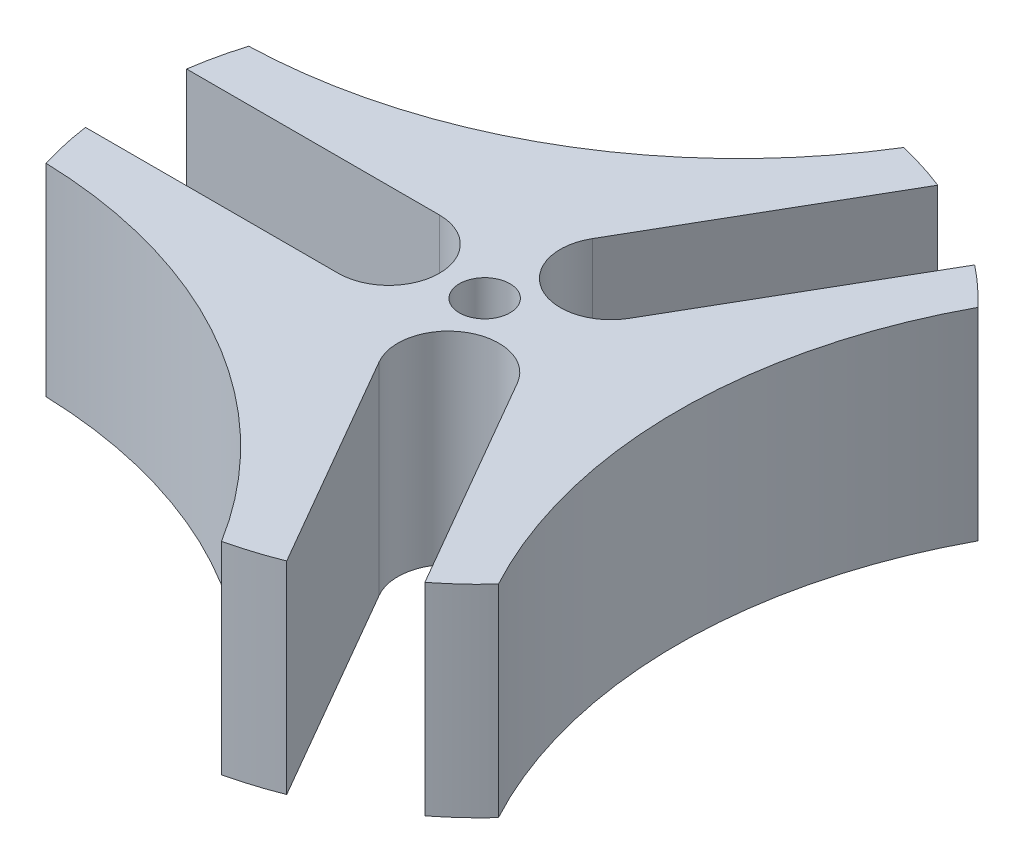
SolidWorks part; units mm, degrees
ref_plane "前基準面" through (0, 0, 0) normal (0, 0, 1) x (1, 0, 0)
ref_plane "上基準面" through (0, 0, 0) normal (0, 1, 0) x (1, 0, 0)
ref_plane "右基準面" through (0, 0, 0) normal (1, 0, 0) x (0, 0, -1)
sketch "草圖1" plane through (0, 0, 0) normal (0, 1, 0) x (1, 0, 0)
  line L0 (0, 0) -> (34.641, 0) construction
  line L1 (34.641, 0) -> (10.8253, 13.75) construction
  line L6 (8.6603, 15) -> (0, 0) construction
  line L7 (0.1554, 5.2692) -> (6.4045, 16.0929)
  line L9 (4.4856, 2.7692) -> (10.7346, 13.5929)
  line L10 (4.4856, -2.7692) -> (10.7346, -13.5929)
  line L11 (0.1554, -5.2692) -> (6.4045, -16.0929)
  line L12 (-4.641, -2.5) -> (-17.1391, -2.5)
  line L13 (-4.641, 2.5) -> (-17.1391, 2.5)
  arc A14 (12.6295, 11.8531) -> (10.7346, 13.5929) centre (0, 0) ccw
  circle A15 centre (34.641, 0) radius 30 construction
  circle A16 centre (0, 0) radius 4.641 construction
  arc A17 (10.8253, 13.75) -> (10.7295, 13.597) centre (8.6603, 15) ccw construction
  arc A18 (0.1554, 5.2692) -> (4.4856, 2.7692) centre (2.3205, 4.0192) ccw
  arc A19 (4.4856, -2.7692) -> (0.1554, -5.2692) centre (2.3205, -4.0192) ccw
  arc A20 (-4.641, -2.5) -> (-4.641, 2.5) centre (-4.641, 0) ccw
  circle A24 centre (4.641, 0) radius 2 construction
  arc A25 (12.6295, 11.8531) -> (12.6295, -11.8531) centre (34.641, 0) ccw
  arc A26 (13.8502, -11.9893) -> (13.8852, 12.0497) centre (34.641, 0) ccw construction
  arc A27 (13.8502, -11.9893) -> (13.8852, 12.0497) centre (0.0486, 0.0503) ccw construction
  arc A28 (3.9503, -16.864) -> (-16.5798, -5.011) centre (-17.3205, -30) ccw
  arc A29 (-16.5798, 5.011) -> (3.9503, 16.864) centre (-17.3205, 30) ccw
  arc A30 (3.9503, -16.864) -> (6.4045, -16.0929) centre (0, 0) ccw
  arc A31 (10.7346, -13.5929) -> (12.6295, -11.8531) centre (0, 0) ccw
  arc A32 (-16.5798, 5.011) -> (-17.1391, 2.5) centre (0, 0) ccw
  arc A33 (-17.1391, -2.5) -> (-16.5798, -5.011) centre (0, 0) ccw
  arc A34 (6.4045, 16.0929) -> (3.9503, 16.864) centre (0, 0) ccw
  circle A35 centre (0.0486, 0.0503) radius 1.25
  point P24 (0, 0)
  point P26 (0, 0)
  point P39 (0, 0)
  dimension "D1" = 60
  dimension "D4" = 24
  dimension "D3" = 90
  dimension "D5" = 4
  dimension "D6" = 30
  dimension "D2" = 5
  dimension "D9" = 2.5
  dimension "D10" = 60
  dimension "D11" = 34.641
  dimension "D12" = 25
  dimension "D13" = 18.315
  dimension "D7" = 3
  dimension "D8" = 3
extrude "填料-伸長1" add sketch "草圖1" along normal blind 10
